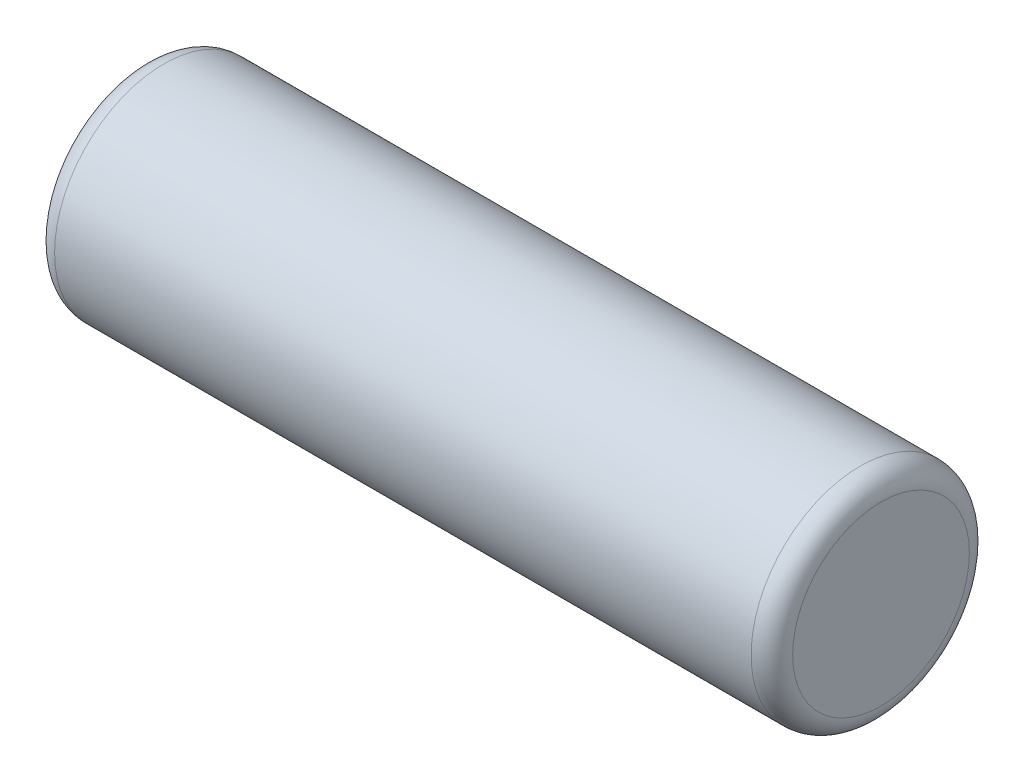
SolidWorks part; units mm, degrees
ref_plane "前视基准面" through (0, 0, 0) normal (0, 0, 1) x (1, 0, 0)
ref_plane "上视基准面" through (0, 0, 0) normal (0, 1, 0) x (1, 0, 0)
ref_plane "右视基准面" through (0, 0, 0) normal (1, 0, 0) x (0, 0, -1)
sketch "草图1" plane through (0, 0, 0) normal (0, 1, 0) x (1, 0, 0)
  line L5 (35.5, 0) -> (-35.5, 0)
  line L6 (-35.5, 0) -> (-35.5, 10.5)
  line L9 (-35.5, 10.5) -> (35.5, 10.5)
  line L10 (35.5, 10.5) -> (35.5, 0)
  point P0 (25.9105, 12.1356)
  point P3 (0, 0)
  dimension "D1" = 71
  dimension "D2" = 10.5
revolve "旋转3" add sketch "草图1" angle 360 about L5
fillet "圆角1" radius 2 1 edges at (-35.5, 0, -10.5)
fillet "圆角2" radius 2 1 edges at (35.5, 0, -10.5)
sketch "草图2" plane through (-35.5, 0, 0) normal (-1, 0, 0) x (0, 0, 1)
  circle A0 centre (0, 0) radius 2.5
  dimension "D1" = 5
extrude "凸台-拉伸1" add sketch "草图2" along normal blind 2
fillet "圆角3" radius 1 1 edges at (-37.5, 0, 2.5)
